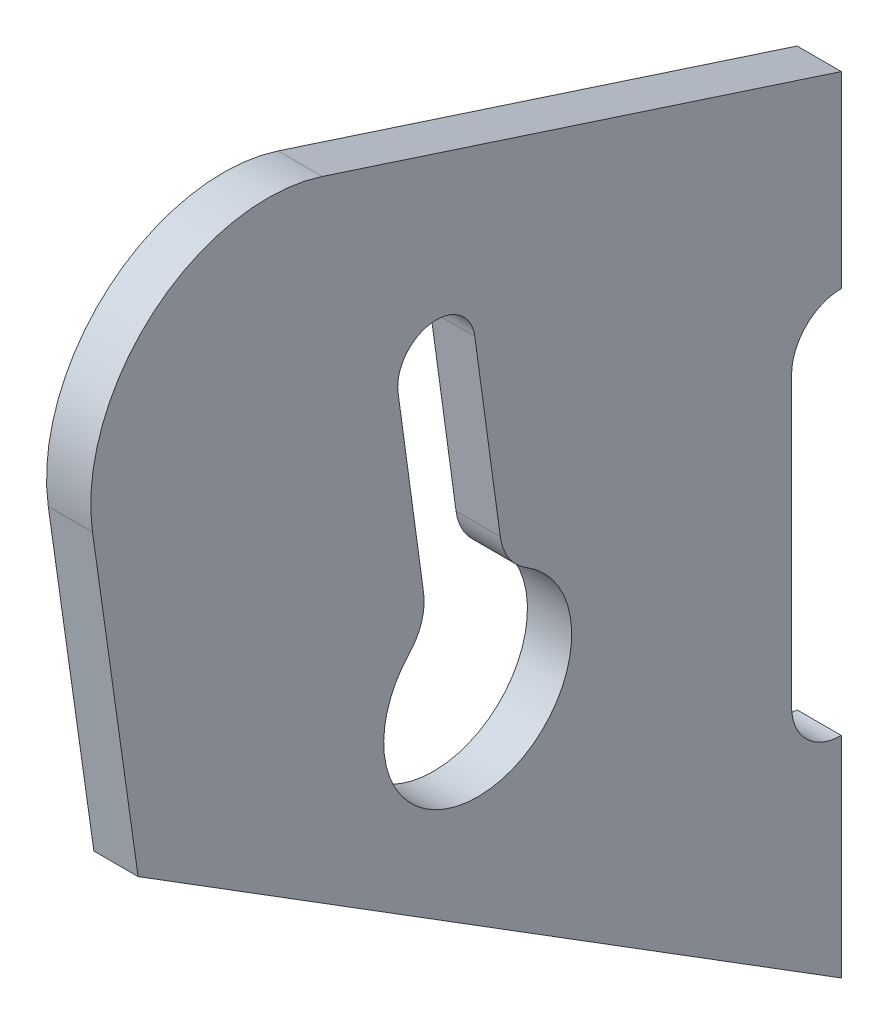
SolidWorks part; units mm, degrees
ref_plane "Front Plane" through (0, 0, 0) normal (1, 0, 0) x (0, 1, 0)
ref_plane "Top Plane" through (0, 0, 0) normal (0, 0, 1) x (0, 1, 0)
ref_plane "Right Plane" through (0, 0, 0) normal (0, 1, 0) x (-1, 0, 0)
sketch "Sketch1" plane through (0, 0, 0) normal (1, 0, 0) x (0, 1, 0)
  line L0 (0, 0) -> (79.4879, 127.2072)
  line L1 (79.4879, 127.2072) -> (137.573, 135.4513)
  line L2 (172.5035, 93.8803) -> (142, 0)
  line L3 (0, 0) -> (142, 0)
  line L4 (47, 0) -> (99, 0) construction
  line L5 (47, 9) -> (99, 9)
  line L6 (47, -9) -> (99, -9)
  line L7 (78.2447, 65.7777) -> (132.7354, 73.2448) construction
  line L8 (77.2943, 72.7129) -> (131.7851, 80.1799)
  line L9 (79.195, 58.8425) -> (133.6858, 66.3096)
  line L10 (132.7354, 73.2448) -> (167.3394, 77.9866) construction
  arc A0 (137.573, 135.4513) -> (172.5035, 93.8803) centre (142.0697, 103.7688) cw
  arc A1 (47, 9) -> (47, -9) centre (47, 0) ccw
  arc A2 (99, -9) -> (99, 9) centre (99, 0) ccw
  circle A3 centre (78.2447, 65.7777) radius 17
  arc A4 (77.2943, 72.7129) -> (79.195, 58.8425) centre (78.2447, 65.7777) ccw
  arc A5 (133.6858, 66.3096) -> (131.7851, 80.1799) centre (132.7354, 73.2448) ccw
  point P9 (73, 0)
  point P14 (188.3525, 142.6585)
  point P17 (105.49, 69.5112)
  point P23 (37.6243, 60.2114)
  dimension "D7" = 32
  dimension "D11" = 34
  dimension "D1" = 150
  dimension "D2" = 58
  dimension "D3" = 52
  dimension "D4" = 47
  dimension "D5" = 108
  dimension "D6" = 150
  dimension "D8" = 9
  dimension "D9" = 142
  dimension "D10" = 55
  dimension "D12" = 14
  dimension "D13" = 71
  dimension "D14" = 41
  dimension "D15" = 82
extrude "Boss-Extrude1" add sketch "Sketch1" along normal mid plane 8 contours A2 L3 L2 A0 L1 L0 A1 L5 A5 L9 A3 L8
fillet "Fillet1" radius 10 2 edges at (0, 92.6428, 74.8162) (0, 94.5435, 60.9458)
